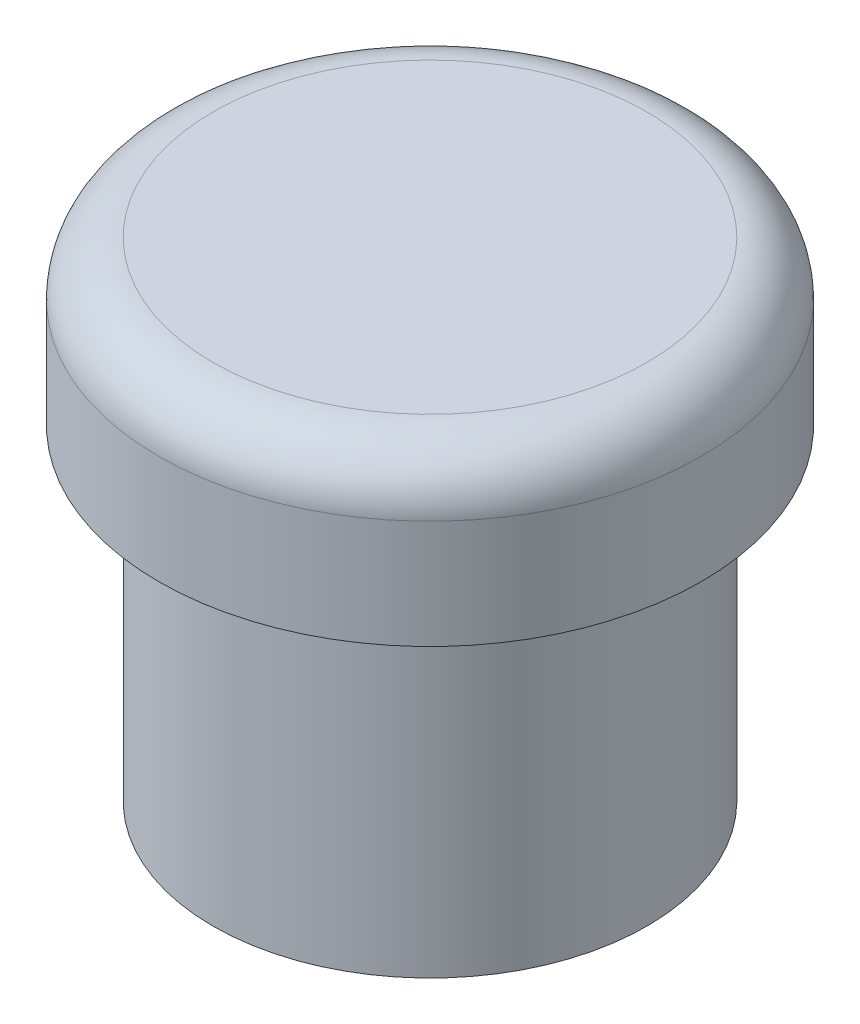
SolidWorks part; units mm, degrees
ref_plane "Front Plane" through (0, 0, 0) normal (0, 0, 1) x (1, 0, 0)
ref_plane "Top Plane" through (0, 0, 0) normal (0, 1, 0) x (1, 0, 0)
ref_plane "Right Plane" through (0, 0, 0) normal (1, 0, 0) x (0, 0, -1)
sketch "Sketch1" plane through (0, 0, 0) normal (0, 1, 0) x (1, 0, 0)
  circle A0 centre (0, 0) radius 1.5875
  circle A1 centre (0, 0) radius 2
  dimension "D1" = 3.175
  dimension "D2" = 4
extrude "Boss-Extrude1" add sketch "Sketch1" along normal blind 3
sketch "Sketch2" plane through (0, 3, 0) normal (0, 1, 0) x (1, 0, 0)
  circle A0 centre (0, 0) radius 2.5
  dimension "D1" = 5
extrude "Boss-Extrude2" add sketch "Sketch2" along normal blind 1.5
fillet "Fillet1" radius 0.5 1 edges at (0, 4.5, 2.5)
